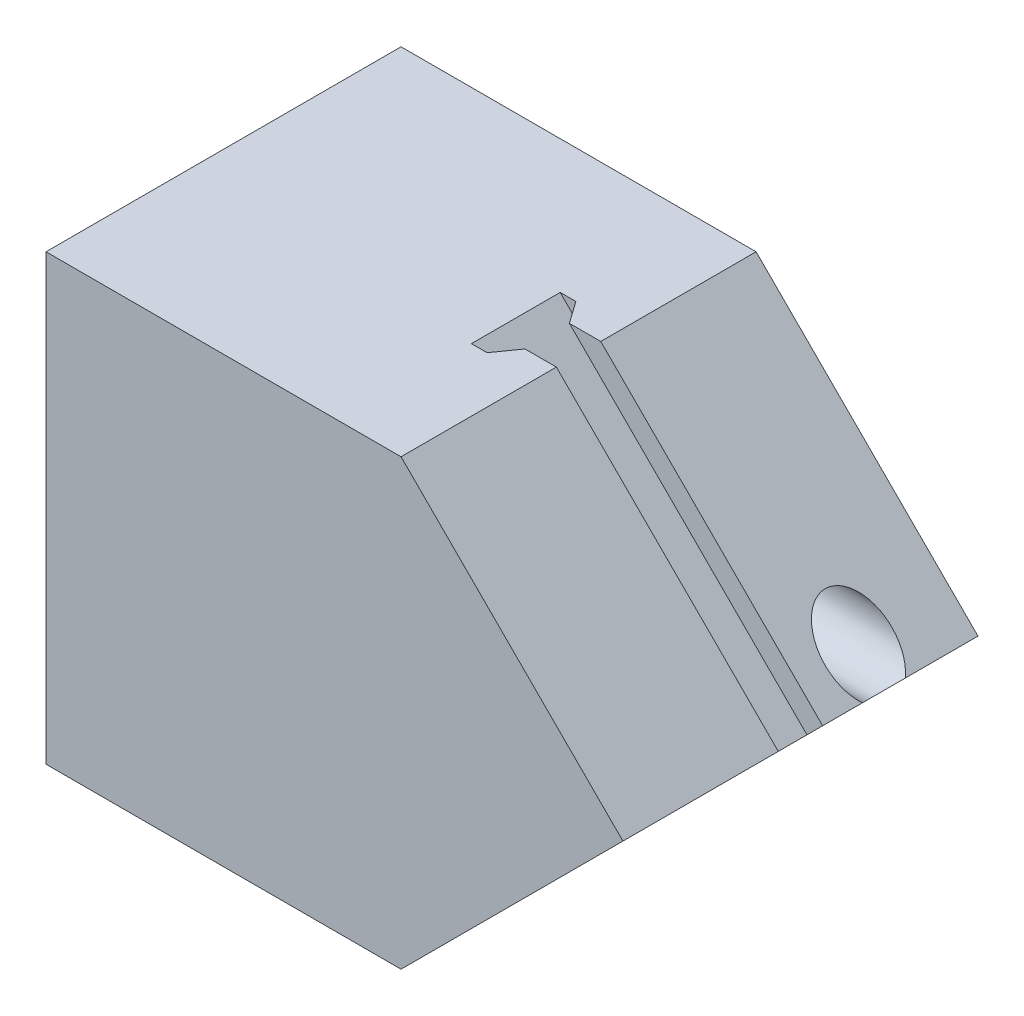
SolidWorks part; units mm, degrees
ref_plane "前视基准面" through (0, 0, 0) normal (0, 0, 1) x (1, 0, 0)
ref_plane "上视基准面" through (0, 0, 0) normal (0, 1, 0) x (1, 0, 0)
ref_plane "右视基准面" through (0, 0, 0) normal (1, 0, 0) x (0, 0, -1)
sketch "草图1" plane through (0, 0, 0) normal (0, 0, 1) x (1, 0, 0)
  line L0 (0, 0) -> (-140, 0) construction
  line L1 (-140, 50) -> (-140, -50)
  line L2 (-140, -50) -> (-50, -50)
  line L3 (-50, -50) -> (0, 0)
  line L4 (-140, 50) -> (-50, 50)
  line L5 (-50, 50) -> (0, 0)
  dimension "D1" = 140
  dimension "D2" = 50
  dimension "D3" = 45
extrude "凸台-拉伸1" add sketch "草图1" along normal mid plane 80
sketch "草图2" plane through (-140, 0, 0) normal (-1, 0, 0) x (0, 0, 1)
  circle A0 centre (-18.8073, 5.7332) radius 7.5
  dimension "D1" = 15
extrude "切除-拉伸1" cut sketch "草图2" against normal through all
ref_plane "基准面1" through (0, 0, 0) normal (0.7071, 0.7071, 0) x (0.7071, -0.7071, 0)
ref_plane "基准面2" through (-50, 50, 0) normal (0.7071, -0.7071, 0) x (0, 0, -1)
sketch "草图3" plane through (-50, 50, 0) normal (0.7071, -0.7071, 0) x (0, 0, -1)
  line L0 (0, 42.5604) -> (0, -85.4955) construction
  line L2 (5, 5) -> (-5, 5)
  line L3 (5, 5) -> (5, -5)
  line L5 (-5, 5) -> (-5, -5)
  line L6 (5, 5) -> (-5, -5) construction
  line L7 (5, -5) -> (-5, 5) construction
  line L8 (5, -5) -> (10, -7.5)
  line L9 (10, -7.5) -> (10, -10)
  line L10 (10, -10) -> (-10, -10)
  line L11 (-10, -10) -> (-10, -7.5)
  line L12 (-10, -7.5) -> (-5, -5)
  point P3 (0, 0)
  dimension "D1" = 10
  dimension "D3" = 10
  dimension "D4" = 10
  dimension "D6" = 2.5
  dimension "D7" = 2.5
extrude "切除-拉伸2" cut sketch "草图3" along normal through all both and the other way through all
sketch "草图4" plane through (0, 0, 40) normal (0, 0, 1) x (1, 0, 0)
  line L0 (-130, -50) -> (-130, -180) construction
  line L1 (-130, -69.6915) -> (-169.0561, -69.6915)
  line L2 (-130, -69.6915) -> (-130, 58.4156)
  line L3 (-130, 58.4156) -> (-169.0561, 58.4156)
  line L4 (-169.0561, -69.6915) -> (-169.0561, 58.4156)
extrude "切除-拉伸3" cut sketch "草图4" against normal through all both and the other way through all
